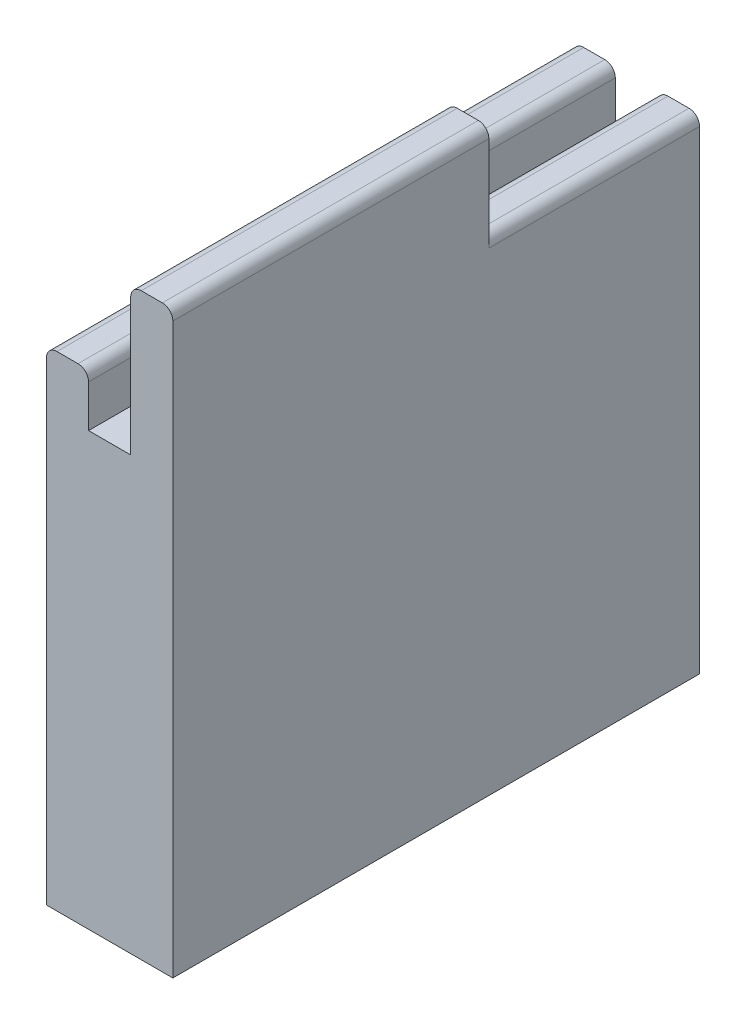
SolidWorks part; units mm, degrees
ref_plane "Plan de face" through (0, 0, 0) normal (0, 0, 1) x (1, 0, 0)
ref_plane "Plan de dessus" through (0, 0, 0) normal (0, 1, 0) x (1, 0, 0)
ref_plane "Plan de droite" through (0, 0, 0) normal (1, 0, 0) x (0, 0, -1)
sketch "Esquisse1" plane through (0, 0, 0) normal (0, 0, 1) x (1, 0, 0)
  line L0 (-4.1207, 2.5) -> (-2.1207, 2.5)
  line L1 (-2.1207, 2.5) -> (-2.1207, 0)
  line L2 (-2.1207, 0) -> (-0.1207, 0)
  line L3 (-0.1207, 0) -> (-0.1207, 2.5)
  line L4 (-0.1207, 2.5) -> (1.8793, 2.5)
  line L5 (1.8793, 2.5) -> (1.8793, -20.5)
  line L6 (1.8793, -20.5) -> (-4.1207, -20.5)
  line L7 (-4.1207, -20.5) -> (-4.1207, 2.5)
  line L8 (-2.1207, 2.5) -> (-0.1207, 2.5) construction
  dimension "D1" = 2
  dimension "D2" = 2
  dimension "D3" = 2
  dimension "D4" = 2.5
  dimension "D5" = 20.5
extrude "Boss.-Extru.1" add sketch "Esquisse1" along normal blind 25
fillet "Congé1" radius 0.5 4 edges at (1.8793, 2.5, 12.5) (-4.1207, 2.5, 12.5) (-0.1207, 2.5, 12.5) (-2.1207, 2.5, 12.5)
sketch "Esquisse2" plane through (1.8793, 0, 0) normal (1, 0, 0) x (0, 0, -1)
  line L1 (-25, 2) -> (-10, 2)
  line L2 (-25, 2) -> (-25, 7)
  line L3 (-25, 7) -> (-10, 7)
  line L4 (-10, 2) -> (-10, 7)
  dimension "D1" = 5
  dimension "15" = 15
extrude "Boss.-Extru.2" add sketch "Esquisse2" against normal blind 2
fillet "Congé2" radius 0.5 2 edges at (1.8793, 7, 17.5) (-0.1207, 7, 17.5)
